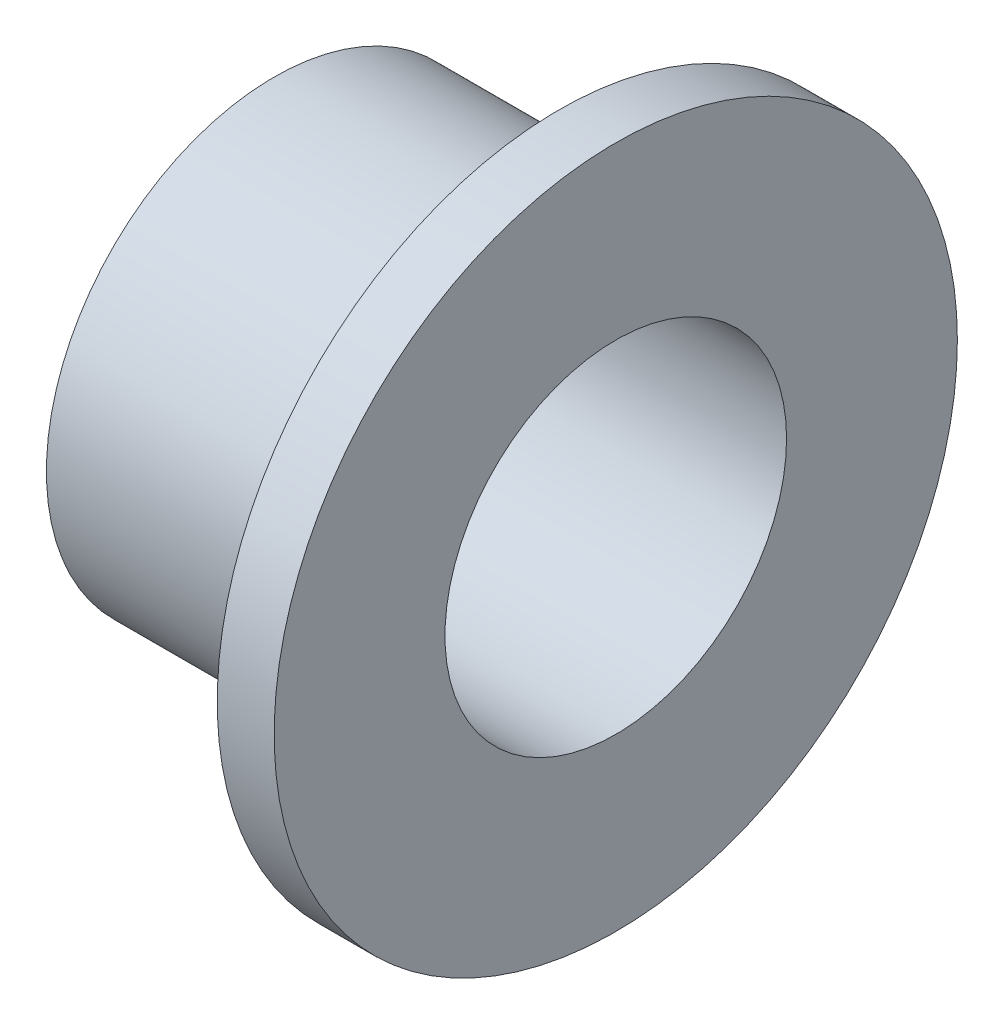
SolidWorks part; units mm, degrees
ref_plane "Alzado" through (0, 0, 0) normal (1, 0, 0) x (0, 1, 0)
ref_plane "Planta" through (0, 0, 0) normal (0, 0, 1) x (0, 1, 0)
ref_plane "Vista lateral" through (0, 0, 0) normal (0, 1, 0) x (-1, 0, 0)
sketch "Croquis1" plane through (0, 0, 0) normal (0, 1, 0) x (-1, 0, 0)
  line L0 (0, 6) -> (0, 3)
  line L1 (0, 3) -> (6, 3)
  line L2 (6, 3) -> (6, 4)
  line L3 (6, 4) -> (1, 4)
  line L4 (1, 4) -> (1, 6)
  line L5 (1, 6) -> (0, 6)
  line L6 (0, 0) -> (6, 0) construction
  point P4 (1, 5.1427)
  dimension "D1" = 6
  dimension "D2" = 12
  dimension "D3" = 1
  dimension "D4" = 6
  dimension "D5" = 8
revolve "Revolución1" add sketch "Croquis1" angle 360 about L6
